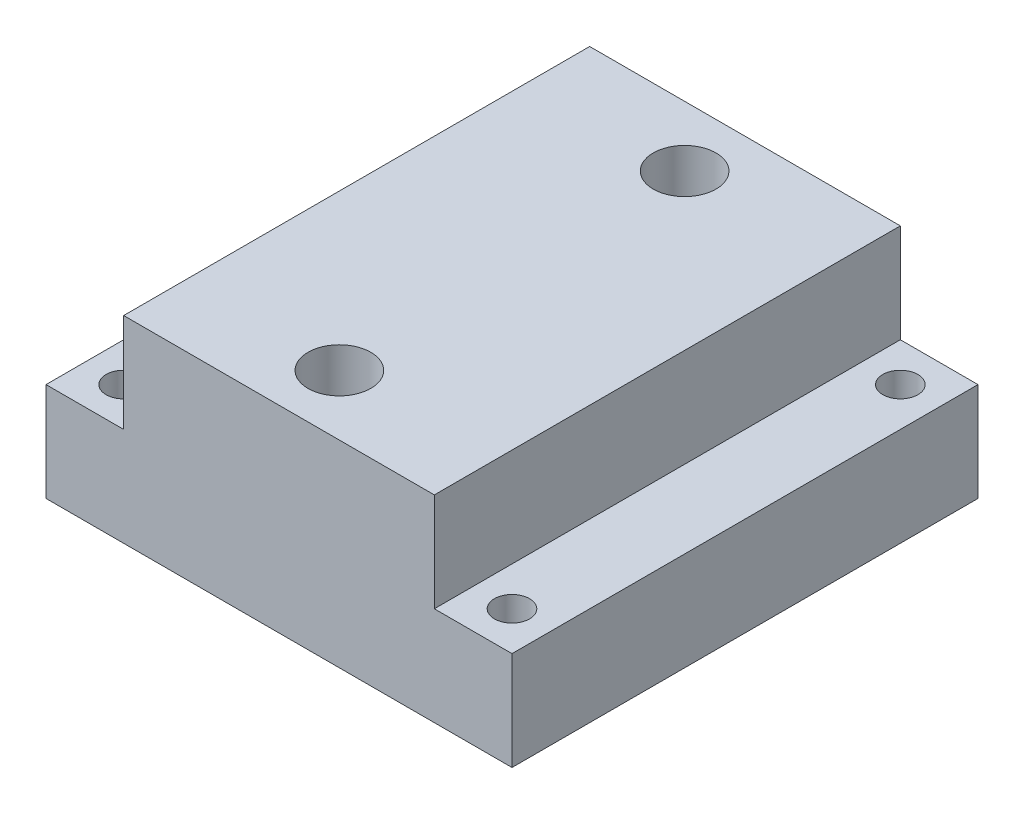
SolidWorks part; units mm, degrees
material "Delrin 2700 NC010, Low Viscosity Acetal Copolymer (SS)"
ref_plane "Front Plane" through (0, 0, 0) normal (0, 0, 1) x (1, 0, 0)
ref_plane "Top Plane" through (0, 0, 0) normal (0, 1, 0) x (1, 0, 0)
ref_plane "Right Plane" through (0, 0, 0) normal (1, 0, 0) x (0, 0, -1)
sketch "Sketch1" plane through (0, 0, 0) normal (0, 0, 1) x (1, 0, 0)
  line L1 (0, 0) -> (30, 0)
  line L2 (0, 0) -> (0, 12.7)
  line L3 (0, 12.7) -> (30, 12.7)
  line L4 (30, 0) -> (30, 12.7)
  dimension "D1" = 12.7
  dimension "D2" = 30
extrude "Boss-Extrude1" add sketch "Sketch1" along normal blind 30
hole_wizard "#2 Clearance Hole1" positions "Sketch3" profile "Sketch2" hole size "#2" standard "ANSI Inch" end condition through all
sketch "Sketch3" plane through (0, 12.7, 0) normal (0, 1, 0) x (1, 0, 0)
  line L0 (2.5, -27.5) -> (2.5, -2.5) construction
  line L1 (2.5, -2.5) -> (27.5, -2.5) construction
  line L2 (27.5, -2.5) -> (27.5, -27.5) construction
  line L3 (27.5, -27.5) -> (2.5, -27.5) construction
  line L5 (15, -2.5) -> (15, 0) construction
  line L6 (30, 0) -> (0, 0) construction
  line L8 (2.5, -15) -> (0, -15) construction
  line L9 (0, -30) -> (0, 0) construction
  point P0 (2.5, -2.5)
  point P2 (27.5, -2.5)
  point P4 (27.5, -27.5)
  point P6 (2.5, -27.5)
  dimension "D1" = 25
  dimension "D2" = 25
sketch "Sketch2" plane through (2.5, 12.7, 2.5) normal (1, 0, 0) x (0, 0, 1)
  line L0 (0, 0) -> (0, 12.7)
  line L1 (0, 12.7) -> (1.1303, 12.7)
  line L2 (1.1303, 12.7) -> (1.1303, 0)
  line L5 (1.1303, 0) -> (0, 0)
  line L11 (0, -6.35) -> (0, 107.95) construction
  dimension "Thru Hole Dia." = 2.2606
  dimension "Thru Hole Depth" = 12.7
sketch "Sketch4" plane through (0, 12.7, 0) normal (0, 1, 0) x (1, 0, 0)
  line L0 (30, 0) -> (0, 0) construction
  line L1 (5, 0) -> (25, 0)
  line L2 (5, 0) -> (5, -30)
  line L3 (5, -30) -> (25, -30)
  line L4 (25, 0) -> (25, -30)
  line L5 (30, -30) -> (0, -30) construction
  line L6 (15, -30) -> (15, 0) construction
  dimension "D1" = 20
extrude "Cut-Extrude1" cut sketch "Sketch4" against normal offset from surface (6.35 mm away) 6.35 flip side to cut up to face at (2.5, 0, 3.6303)
hole_wizard "#10-32 Tapped Hole1" positions "Sketch6" profile "Sketch5" tap size "#10-32" standard "ANSI Inch" end condition through all
sketch "Sketch6" plane through (0, 12.7, 0) normal (0, 1, 0) x (1, 0, 0)
  line L0 (15, -30) -> (15, -26.1125) construction
  line L1 (25, -30) -> (5, -30) construction
  line L2 (15, -26.1125) -> (15, -3.8875) construction
  line L4 (15, -15) -> (25, -15) construction
  line L5 (25, -30) -> (25, 0) construction
  point P0 (15, -3.8875)
  point P2 (15, -26.1125)
  dimension "D1" = 22.225
sketch "Sketch5" plane through (15, 12.7, 3.8875) normal (1, 0, 0) x (0, 0, 1)
  line L0 (0, 0) -> (0, 12.7)
  line L1 (0, 12.7) -> (2.0193, 12.7)
  line L2 (2.0193, 12.7) -> (2.0193, 0)
  line L5 (2.0193, 0) -> (0, 0)
  line L11 (0, -6.35) -> (0, 107.95) construction
  dimension "Thru Tap Drill Dia." = 4.0386
  dimension "Thru Tap Drill Depth" = 12.7
cosmetic thread "Hole Thread1" parameters "D2"=4.826
cosmetic thread "Hole Thread2" parameters "D2"=4.826
